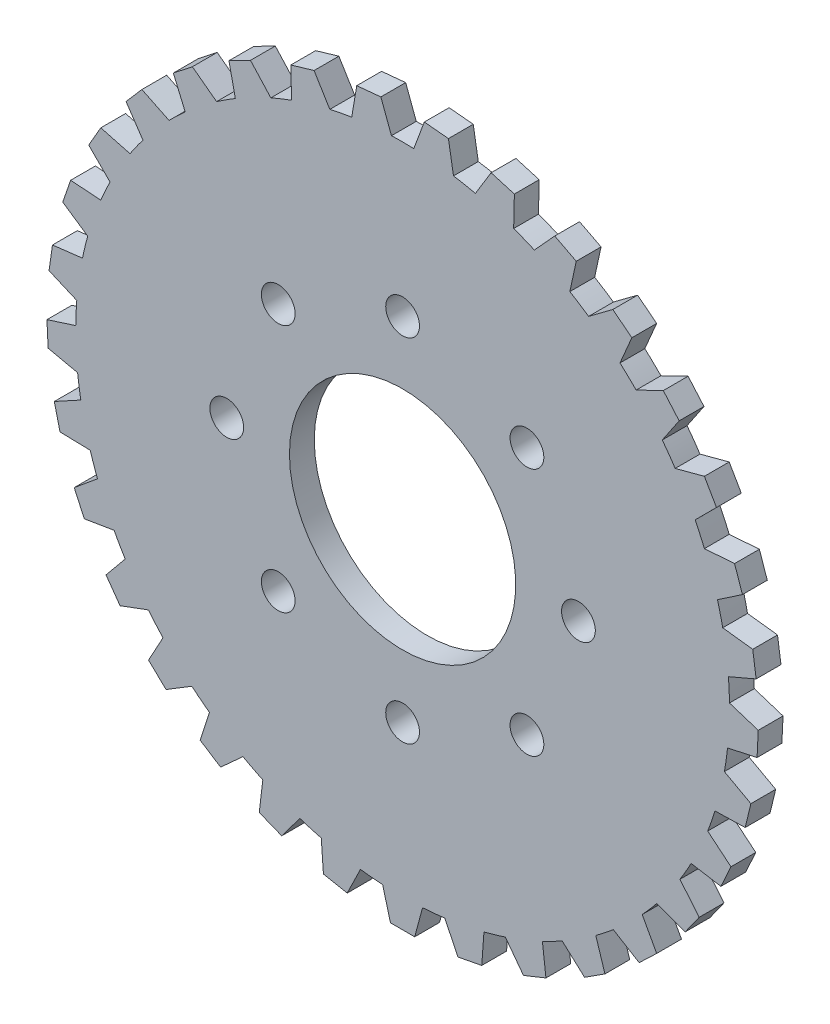
SolidWorks part; units mm, degrees
ref_plane "Front Plane" through (0, 0, 0) normal (0, 0, 1) x (1, 0, 0)
ref_plane "Top Plane" through (0, 0, 0) normal (0, 1, 0) x (1, 0, 0)
ref_plane "Right Plane" through (0, 0, 0) normal (1, 0, 0) x (0, 0, -1)
sketch "Sketch1" plane through (0, 0, 0) normal (0, 0, 1) x (1, 0, 0)
  line L1 (7.9169, 82.909) -> (8.648, 90.5658) construction
  line L3 (2.854, 83.6163) -> (5.5632, 90.8604)
  line L4 (5.5632, 90.8604) -> (11.7328, 90.2713)
  line L6 (7.7778, 81.4525) -> (7.9169, 82.909) construction
  line L7 (13.022, 82.6454) -> (11.7328, 90.2713)
  line L8 (18.6269, 81.5651) -> (22.6581, 88.1656)
  line L9 (28.4275, 78.6874) -> (28.6047, 86.4195)
  line L10 (22.6581, 88.1656) -> (28.6047, 86.4195)
  line L11 (33.7266, 76.566) -> (38.9341, 82.2842)
  line L12 (42.8054, 71.8855) -> (44.4428, 79.4443)
  line L13 (38.9341, 82.2842) -> (44.4428, 79.4443)
  line L14 (47.6074, 68.7995) -> (53.8029, 73.4289)
  line L15 (55.6363, 62.4855) -> (58.6746, 69.5978)
  line L16 (53.8029, 73.4289) -> (58.6746, 69.5978)
  line L17 (59.7674, 58.5465) -> (66.7271, 61.9197)
  line L18 (66.4563, 50.827) -> (70.7857, 57.2358)
  line L19 (66.7271, 61.9197) -> (70.7857, 57.2358)
  line L20 (69.7673, 46.1774) -> (77.2397, 48.1726)
  line L21 (74.8745, 37.3316) -> (80.3385, 42.8052)
  line L22 (77.2397, 48.1726) -> (80.3385, 42.8052)
  line L23 (77.2457, 32.1394) -> (84.9606, 32.6843)
  line L24 (80.5864, 22.4869) -> (86.9876, 26.8275)
  line L25 (84.9606, 32.6843) -> (86.9876, 26.8275)
  line L26 (81.9322, 16.9397) -> (89.6108, 16.0148)
  line L27 (83.3858, 6.8294) -> (90.4928, 9.8802)
  line L28 (89.6108, 16.0148) -> (90.4928, 9.8802)
  line L29 (83.6574, 1.1278) -> (91.0222, -1.2336)
  line L30 (83.1714, -9.0749) -> (90.7273, -7.4242)
  line L31 (91.0222, -1.2336) -> (90.7273, -7.4242)
  line L32 (82.359, -14.7248) -> (89.1438, -18.4373)
  line L33 (79.9509, -24.6512) -> (87.6827, -24.4603)
  line L34 (89.1438, -18.4373) -> (87.6827, -24.4603)
  line L35 (78.084, -30.0453) -> (84.0436, -34.9747)
  line L36 (73.8409, -39.3365) -> (81.469, -40.6123)
  line L37 (84.0436, -34.9747) -> (81.469, -40.6123)
  line L38 (70.9868, -44.2798) -> (75.9058, -50.2481)
  line L39 (65.062, -52.6001) -> (72.3108, -55.2965)
  line L40 (75.9058, -50.2481) -> (72.3108, -55.2965)
  line L41 (61.324, -56.914) -> (65.0246, -63.7053)
  line L42 (53.9316, -63.9626) -> (60.5391, -67.9822)
  line L43 (65.0246, -63.7053) -> (60.5391, -67.9822)
  line L44 (49.4448, -67.4911) -> (51.7932, -74.86)
  line L45 (40.852, -73.0133) -> (46.5794, -78.2107)
  line L46 (51.7932, -74.86) -> (46.5794, -78.2107)
  line L47 (35.7784, -75.6289) -> (36.6899, -83.3091)
  line L48 (26.2959, -79.4252) -> (30.9362, -85.6126)
  line L49 (36.6899, -83.3091) -> (30.9362, -85.6126)
  line L50 (20.819, -81.0333) -> (20.2605, -88.7472)
  line L51 (10.7893, -82.9664) -> (14.1748, -89.9202)
  line L52 (20.2605, -88.7472) -> (14.1748, -89.9202)
  line L53 (5.1071, -83.509) -> (3.0988, -90.9778)
  line L54 (-5.1071, -83.509) -> (-3.0988, -90.9778)
  line L55 (3.0988, -90.9778) -> (-3.0988, -90.9778)
  line L56 (-10.7893, -82.9664) -> (-14.1748, -89.9202)
  line L57 (-20.819, -81.0333) -> (-20.2605, -88.7472)
  line L58 (-14.1748, -89.9202) -> (-20.2605, -88.7472)
  line L59 (-26.2959, -79.4252) -> (-30.9362, -85.6126)
  line L60 (-35.7784, -75.6289) -> (-36.6899, -83.3091)
  line L61 (-30.9362, -85.6126) -> (-36.6899, -83.3091)
  line L62 (-40.852, -73.0133) -> (-46.5794, -78.2107)
  line L63 (-49.4448, -67.4911) -> (-51.7932, -74.86)
  line L64 (-46.5794, -78.2107) -> (-51.7932, -74.86)
  line L65 (-53.9316, -63.9626) -> (-60.5391, -67.9822)
  line L66 (-61.324, -56.914) -> (-65.0246, -63.7053)
  line L67 (-60.5391, -67.9822) -> (-65.0246, -63.7053)
  line L68 (-65.062, -52.6001) -> (-72.3108, -55.2965)
  line L69 (-70.9868, -44.2798) -> (-75.9058, -50.2481)
  line L70 (-72.3108, -55.2965) -> (-75.9058, -50.2481)
  line L71 (-73.8409, -39.3365) -> (-81.469, -40.6123)
  line L72 (-78.084, -30.0453) -> (-84.0436, -34.9747)
  line L73 (-81.469, -40.6123) -> (-84.0436, -34.9747)
  line L74 (-79.9509, -24.6512) -> (-87.6827, -24.4603)
  line L75 (-82.359, -14.7248) -> (-89.1438, -18.4373)
  line L76 (-87.6827, -24.4603) -> (-89.1438, -18.4373)
  line L77 (-83.1714, -9.0749) -> (-90.7273, -7.4242)
  line L78 (-83.6574, 1.1278) -> (-91.0222, -1.2336)
  line L79 (-90.7273, -7.4242) -> (-91.0222, -1.2336)
  line L80 (-83.3858, 6.8294) -> (-90.4928, 9.8802)
  line L81 (-81.9322, 16.9397) -> (-89.6108, 16.0148)
  line L82 (-90.4928, 9.8802) -> (-89.6108, 16.0148)
  line L83 (-80.5864, 22.4869) -> (-86.9876, 26.8275)
  line L84 (-77.2457, 32.1394) -> (-84.9606, 32.6843)
  line L85 (-86.9876, 26.8275) -> (-84.9606, 32.6843)
  line L86 (-74.8745, 37.3316) -> (-80.3385, 42.8052)
  line L87 (-69.7673, 46.1774) -> (-77.2397, 48.1726)
  line L88 (-80.3385, 42.8052) -> (-77.2397, 48.1726)
  line L89 (-66.4563, 50.827) -> (-70.7857, 57.2358)
  line L90 (-59.7674, 58.5465) -> (-66.7271, 61.9197)
  line L91 (-70.7857, 57.2358) -> (-66.7271, 61.9197)
  line L92 (-55.6363, 62.4855) -> (-58.6746, 69.5978)
  line L93 (-47.6074, 68.7995) -> (-53.8029, 73.4289)
  line L94 (-58.6746, 69.5978) -> (-53.8029, 73.4289)
  line L95 (-42.8054, 71.8855) -> (-44.4428, 79.4443)
  line L96 (-33.7266, 76.566) -> (-38.9341, 82.2842)
  line L97 (-44.4428, 79.4443) -> (-38.9341, 82.2842)
  line L98 (-28.4275, 78.6874) -> (-28.6047, 86.4195)
  line L99 (-18.6269, 81.5651) -> (-22.6581, 88.1656)
  line L100 (-28.6047, 86.4195) -> (-22.6581, 88.1656)
  line L101 (-13.022, 82.6454) -> (-11.7328, 90.2713)
  line L102 (-2.854, 83.6163) -> (-5.5632, 90.8604)
  line L103 (-11.7328, 90.2713) -> (-5.5632, 90.8604)
  arc A0 (-42.8054, 71.8855) -> (-47.6074, 68.7995) centre (0, 0) ccw
  arc A35 (-66.4563, 50.827) -> (-69.7673, 46.1774) centre (0, 0) ccw
  arc A37 (-28.4275, 78.6874) -> (-33.7266, 76.566) centre (0, 0) ccw
  arc A39 (-13.022, 82.6454) -> (-18.6269, 81.5651) centre (0, 0) ccw
  arc A41 (2.854, 83.6163) -> (-2.854, 83.6163) centre (0, 0) ccw
  arc A42 (-55.6363, 62.4855) -> (-59.7674, 58.5465) centre (0, 0) ccw
  arc A44 (-74.8745, 37.3316) -> (-77.2457, 32.1394) centre (0, 0) ccw
  arc A46 (-80.5864, 22.4869) -> (-81.9322, 16.9397) centre (0, 0) ccw
  arc A48 (-83.3858, 6.8294) -> (-83.6574, 1.1278) centre (0, 0) ccw
  arc A50 (-83.1714, -9.0749) -> (-82.359, -14.7248) centre (0, 0) ccw
  arc A52 (-79.9509, -24.6512) -> (-78.084, -30.0453) centre (0, 0) ccw
  arc A54 (-73.8409, -39.3365) -> (-70.9868, -44.2798) centre (0, 0) ccw
  arc A56 (-65.062, -52.6001) -> (-61.324, -56.914) centre (0, 0) ccw
  arc A58 (-53.9316, -63.9626) -> (-49.4448, -67.4911) centre (0, 0) ccw
  arc A60 (-40.852, -73.0133) -> (-35.7784, -75.6289) centre (0, 0) ccw
  arc A63 (-26.2959, -79.4252) -> (-20.819, -81.0333) centre (0, 0) ccw
  arc A64 (-10.7893, -82.9664) -> (-5.1071, -83.509) centre (0, 0) ccw
  arc A66 (20.819, -81.0333) -> (26.2959, -79.4252) centre (0, 0) ccw
  arc A68 (5.1071, -83.509) -> (10.7893, -82.9664) centre (0, 0) ccw
  arc A70 (35.7784, -75.6289) -> (40.852, -73.0133) centre (0, 0) ccw
  arc A72 (49.4448, -67.4911) -> (53.9316, -63.9626) centre (0, 0) ccw
  arc A74 (61.324, -56.914) -> (65.062, -52.6001) centre (0, 0) ccw
  arc A76 (70.9868, -44.2798) -> (73.8409, -39.3365) centre (0, 0) ccw
  arc A78 (78.084, -30.0453) -> (79.9509, -24.6512) centre (0, 0) ccw
  arc A80 (82.359, -14.7248) -> (83.1714, -9.0749) centre (0, 0) ccw
  arc A82 (83.6574, 1.1278) -> (83.3858, 6.8294) centre (0, 0) ccw
  arc A84 (81.9322, 16.9397) -> (80.5864, 22.4869) centre (0, 0) ccw
  arc A86 (77.2457, 32.1394) -> (74.8745, 37.3316) centre (0, 0) ccw
  arc A90 (69.7673, 46.1774) -> (66.4563, 50.827) centre (0, 0) ccw
  arc A92 (59.7674, 58.5465) -> (55.6363, 62.4855) centre (0, 0) ccw
  arc A94 (47.6074, 68.7995) -> (42.8054, 71.8855) centre (0, 0) ccw
  arc A95 (33.7266, 76.566) -> (28.4275, 78.6874) centre (0, 0) ccw
  arc A99 (18.6269, 81.5651) -> (13.022, 82.6454) centre (0, 0) ccw
  point P72 (0, 0)
  point P208 (0, 0)
  dimension "D1" = 167.33
  dimension "D4" = 33
extrude "Boss-Extrude1" add sketch "Sketch1" along normal blind 6.35
sketch "Sketch2" plane through (0, 0, 0) normal (0, 0, -1) x (-1, 0, 0)
  line L0 (0, 0) -> (0, 45.0088) construction
  circle A0 centre (0, 0) radius 28.956
  circle A1 centre (0, 45.0088) radius 4.318
  circle A12 centre (31.826, 31.826) radius 4.318
  circle A13 centre (45.0088, 0) radius 4.318
  circle A14 centre (31.826, -31.826) radius 4.318
  circle A15 centre (0, -45.0088) radius 4.318
  circle A16 centre (-31.826, -31.826) radius 4.318
  circle A17 centre (-45.0088, 0) radius 4.318
  circle A18 centre (-31.826, 31.826) radius 4.318
  point P17 (-4.3377, 2.5044)
  point P18 (0, 0)
  point P24 (0, 0)
  dimension "D1" = 57.912
  dimension "D3" = 8.636
  dimension "D2" = 45.0088
  dimension "D4" = 8
extrude "Cut-Extrude1" cut sketch "Sketch2" against normal through all
